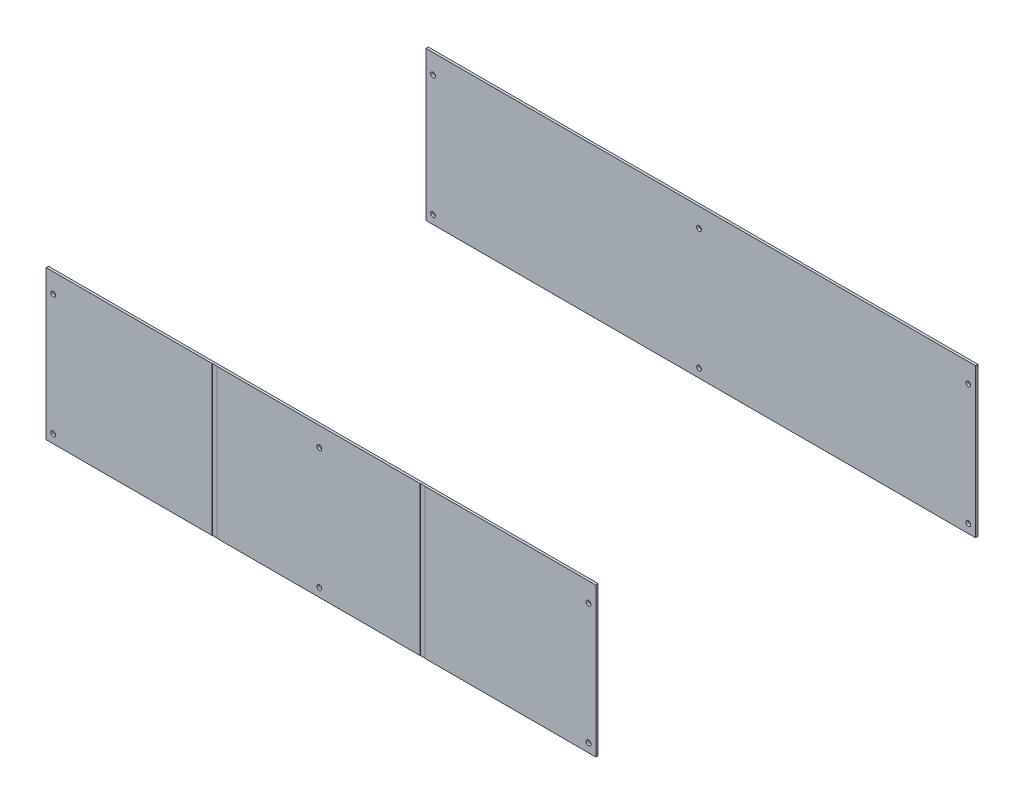
SolidWorks part; units mm, degrees
ref_plane "Front Plane" through (0, 0, 0) normal (0, 0, 1) x (1, 0, 0)
ref_plane "Top Plane" through (0, 0, 0) normal (0, 1, 0) x (1, 0, 0)
ref_plane "Right Plane" through (0, 0, 0) normal (1, 0, 0) x (0, 0, -1)
sketch "Sketch1" plane through (0, 0, 0) normal (0, 0, 1) x (1, 0, 0)
  line L1 (-568.25, 154) -> (568.25, 154)
  line L2 (-568.25, 154) -> (-568.25, -154)
  line L3 (-568.25, -154) -> (568.25, -154)
  line L4 (568.25, 154) -> (568.25, -154)
  line L5 (-568.25, 154) -> (568.25, -154) construction
  line L6 (-568.25, -154) -> (568.25, 154) construction
  point P0 (0, 0)
  dimension "D1" = 1136.5
  dimension "D2" = 308
extrude "Boss-Extrude1" add sketch "Sketch1" along normal blind 5
sketch "Sketch2" plane through (0, 0, 5) normal (0, 0, 1) x (1, 0, 0)
  line L1 (568.25, 154) -> (-568.25, 154) construction
  line L2 (-215, 154) -> (-215, -154)
  line L3 (-568.25, -154) -> (568.25, -154) construction
  line L5 (215, 154) -> (215, -154)
extrude "Cut-Extrude-Thin1" cut sketch "Sketch2" against normal blind 0.5 thin
sketch "Sketch3" plane through (0, 0, 5) normal (0, 0, 1) x (1, 0, 0)
  line L0 (-568.25, 154) -> (-553.25, 154) construction
  line L1 (-225, 154) -> (-568.25, 154) construction
  line L2 (-553.25, 114) -> (-553.25, 154) construction
  circle A0 centre (-553.25, 114) radius 5
  circle A1 centre (-553.25, -136) radius 5
  point P5 (-553.25, 114)
  point P11 (-553.25, -136)
  dimension "D3" = 10
  dimension "D1" = 15
  dimension "D2" = 40
  dimension "D4" = 250
extrude "Cut-Extrude1" cut sketch "Sketch3" against normal through all
ref_plane "Plane3" through (-553.25, 0, 0) normal (-1, 0, 0) x (0, 0, 1)
ref_plane "Plane4" through (-3.25, 0, 0) normal (-1, 0, 0) x (0, 0, 1)
ref_plane "Plane5" through (-278.25, 0, 0) normal (-1, 0, 0) x (0, 0, 1)
mirror "Mirror3" about plane through (-278.25, 0, 0) normal (-1, 0, 0) of "Cut-Extrude1"
ref_plane "Plane6" through (0, 0, 0) normal (-1, 0, 0) x (0, 0, 1)
mirror "Mirror4" about plane through (0, 0, 0) normal (-1, 0, 0) of "Cut-Extrude1"
ref_plane "Plane7" through (0, 0, -390) normal (0, 0, -1) x (-1, 0, 0)
mirror "Mirror6" about plane through (0, 0, -390) normal (0, 0, -1) of bodies 107
